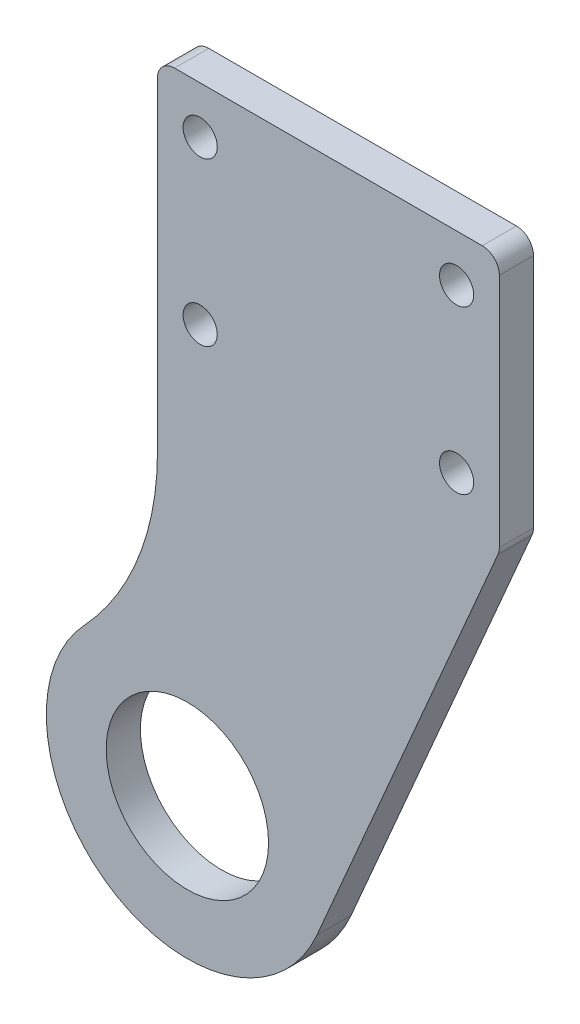
SolidWorks part; units mm, degrees
material "Thornel Mat VMA"
ref_plane "前视基准面" through (0, 0, 0) normal (0, 0, 1) x (1, 0, 0)
ref_plane "上视基准面" through (0, 0, 0) normal (0, 1, 0) x (1, 0, 0)
ref_plane "右视基准面" through (0, 0, 0) normal (1, 0, 0) x (0, 0, -1)
sketch "草图1" plane through (0, 0, 0) normal (0, 0, 1) x (1, 0, 0)
  line L0 (-16.5, 0) -> (-16.5, 73)
  line L1 (-16.5, 73) -> (16.5, 73)
  line L2 (16.5, 73) -> (16.5, 0)
  line L3 (-16.5, 43) -> (40.5902, 43) construction
  circle A0 centre (0, 0) radius 9.5
  arc A1 (-16.5, 0) -> (16.5, 0) centre (0, 0) ccw
  dimension "D1" = 19
  dimension "D2" = 7
  dimension "D3" = 43
  dimension "D4" = 30
extrude "凸台-拉伸1" add sketch "草图1" along normal blind 4
sketch "草图2" plane through (0, 0, 4) normal (0, 0, 1) x (1, 0, 0)
  line L1 (16.5, 73) -> (36.5, 73)
  line L2 (16.5, 73) -> (16.5, 43)
  line L3 (16.5, 43) -> (36.5, 43)
  line L4 (36.5, 73) -> (36.5, 43)
  dimension "D1" = 30
  dimension "D2" = 20
extrude "凸台-拉伸2" add sketch "草图2" against normal up to surface (4 mm away) up to face at (0, 32.375, 0)
sketch "草图3" plane through (0, 0, 4) normal (0, 0, 1) x (1, 0, 0)
  line L0 (-15.7073, 5.0529) -> (-3.5, 43)
  line L1 (-3.5, 43) -> (-3.5, 73)
  line L2 (36.5, 73) -> (-16.5, 73) construction
  line L3 (-3.5, 73) -> (-16.5, 73)
  line L4 (-16.5, 73) -> (-16.5, 0)
  line L5 (36.5, 43) -> (36.5, 73) construction
  arc A0 (-15.7073, 5.0529) -> (-16.5, 0) centre (0, 0) ccw
  point P13 (0, 0)
  dimension "D1" = 33
  dimension "D2" = 30
  dimension "D3" = 40
extrude "切除-拉伸1" cut sketch "草图3" against normal up to surface (4 mm away) up to face at (12.1667, 35.9167, 0)
sketch "草图4" plane through (0, 0, 0) normal (0, 0, -1) x (-1, 0, 0)
  line L0 (-36.5, 43) -> (-15.1526, -6.5307)
  line L1 (-36.5, 43) -> (-16.5, 43)
  line L2 (-16.5, 43) -> (-9.5, 0)
  line L3 (-9.5, 0) -> (-15.1526, -6.5307)
  line L4 (-9.5, 0) -> (0, 0) construction
  arc A0 (-16.5, 0) -> (15.7073, 5.0529) centre (0, 0) ccw construction
  circle A1 centre (0, 0) radius 9.5 construction
extrude "凸台-拉伸3" add sketch "草图4" against normal up to surface (4 mm away) up to face at (11.477, 37.318, 4)
sketch "草图5" plane through (0, 0, 4) normal (0, 0, 1) x (1, 0, 0)
  line L0 (-3.5, 43) -> (-3.5, 33)
  line L1 (-3.5, 43) -> (-15.7073, 5.0529)
  arc A0 (-12.0668, 11.2536) -> (-3.5, 33) centre (-35.3846, 33) ccw
  arc A3 (-15.7073, 5.0529) -> (15.1526, -6.5307) centre (0, 0) ccw construction
  arc A4 (-12.0668, 11.2536) -> (-15.7073, 5.0529) centre (0, 0) ccw
  dimension "D2" = 10
extrude "切除-拉伸2" cut sketch "草图5" against normal up to surface (4 mm away) up to face at (9.9874, 35.9689, 0)
sketch "草图6" plane through (0, 0, 0) normal (0, 0, -1) x (-1, 0, 0)
  line L0 (3.5, 73) -> (3.5, 33) construction
  line L1 (-31.5, 48.5) -> (-1.5, 48.5) construction
  line L2 (-31.5, 48.5) -> (-31.5, 67.5) construction
  line L3 (-31.5, 67.5) -> (-1.5, 67.5) construction
  line L4 (-1.5, 48.5) -> (-1.5, 67.5) construction
  line L5 (-16.5, 67.5) -> (-16.5, 48.5) construction
  line L6 (-31.5, 58) -> (-1.5, 58) construction
  line L7 (-16.5, 73) -> (-16.5, 67.5) construction
  line L8 (-36.5, 73) -> (3.5, 73) construction
  circle A0 centre (-31.5, 67.5) radius 2
  circle A1 centre (-1.5, 67.5) radius 2
  circle A2 centre (-31.5, 48.5) radius 2
  circle A3 centre (-1.5, 48.5) radius 2
  point P0 (-16.5, 58)
  dimension "D4" = 4
  dimension "D1" = 5
  dimension "D2" = 5.5
  dimension "D3" = 5.5
extrude "切除-拉伸3" cut sketch "草图6" against normal up to surface (4 mm away) up to face at (9.5, 0, 4)
fillet "圆角1" radius 2 3 edges at (36.5, 43, 2) (36.5, 73, 2) (-3.5, 73, 2)
